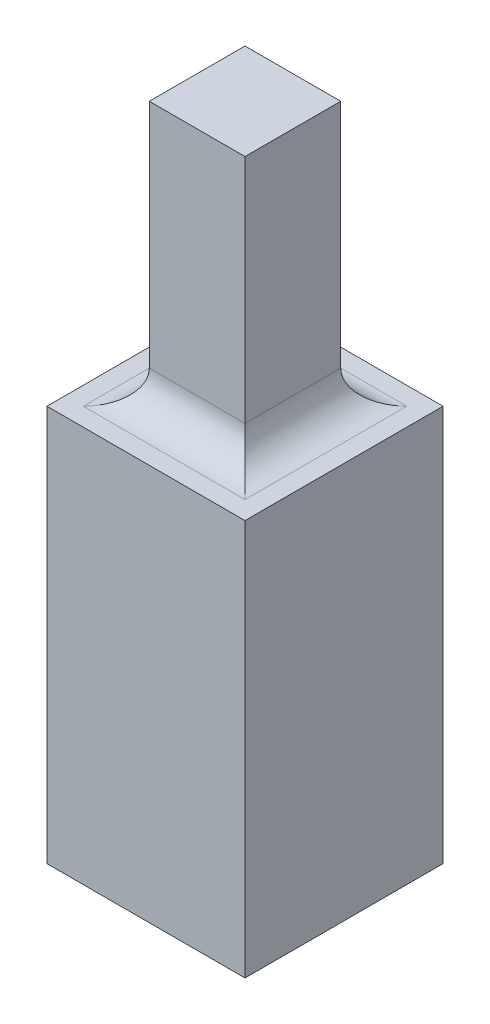
SolidWorks part; units mm, degrees
ref_plane "Front Plane" through (0, 0, 0) normal (0, 0, 1) x (1, 0, 0)
ref_plane "Top Plane" through (0, 0, 0) normal (0, 1, 0) x (1, 0, 0)
ref_plane "Right Plane" through (0, 0, 0) normal (1, 0, 0) x (0, 0, -1)
sketch "Sketch1" plane through (0, 0, 0) normal (0, 1, 0) x (1, 0, 0)
  line L1 (-15, -15) -> (15, -15)
  line L2 (-15, -15) -> (-15, 15)
  line L3 (-15, 15) -> (15, 15)
  line L4 (15, -15) -> (15, 15)
  line L5 (-15, -15) -> (15, 15) construction
  line L6 (-15, 15) -> (15, -15) construction
  point P0 (0, 0)
  dimension "D1" = 30
  dimension "D2" = 30
extrude "Boss-Extrude1" add sketch "Sketch1" along normal blind 60
sketch "Sketch2" plane through (0, 60, 0) normal (0, 1, 0) x (1, 0, 0)
  line L1 (-7.25, -7.25) -> (7.25, -7.25)
  line L2 (-7.25, -7.25) -> (-7.25, 7.25)
  line L3 (-7.25, 7.25) -> (7.25, 7.25)
  line L4 (7.25, -7.25) -> (7.25, 7.25)
  line L5 (-7.25, -7.25) -> (7.25, 7.25) construction
  line L6 (-7.25, 7.25) -> (7.25, -7.25) construction
  point P0 (0, 0)
  dimension "D1" = 14.5
  dimension "D2" = 14.5
extrude "Boss-Extrude2" add sketch "Sketch2" along normal blind 40
fillet "Fillet1" radius 5 4 edges at (7.25, 60, 0) (0, 60, -7.25) (-7.25, 60, 0) (0, 60, 7.25)
